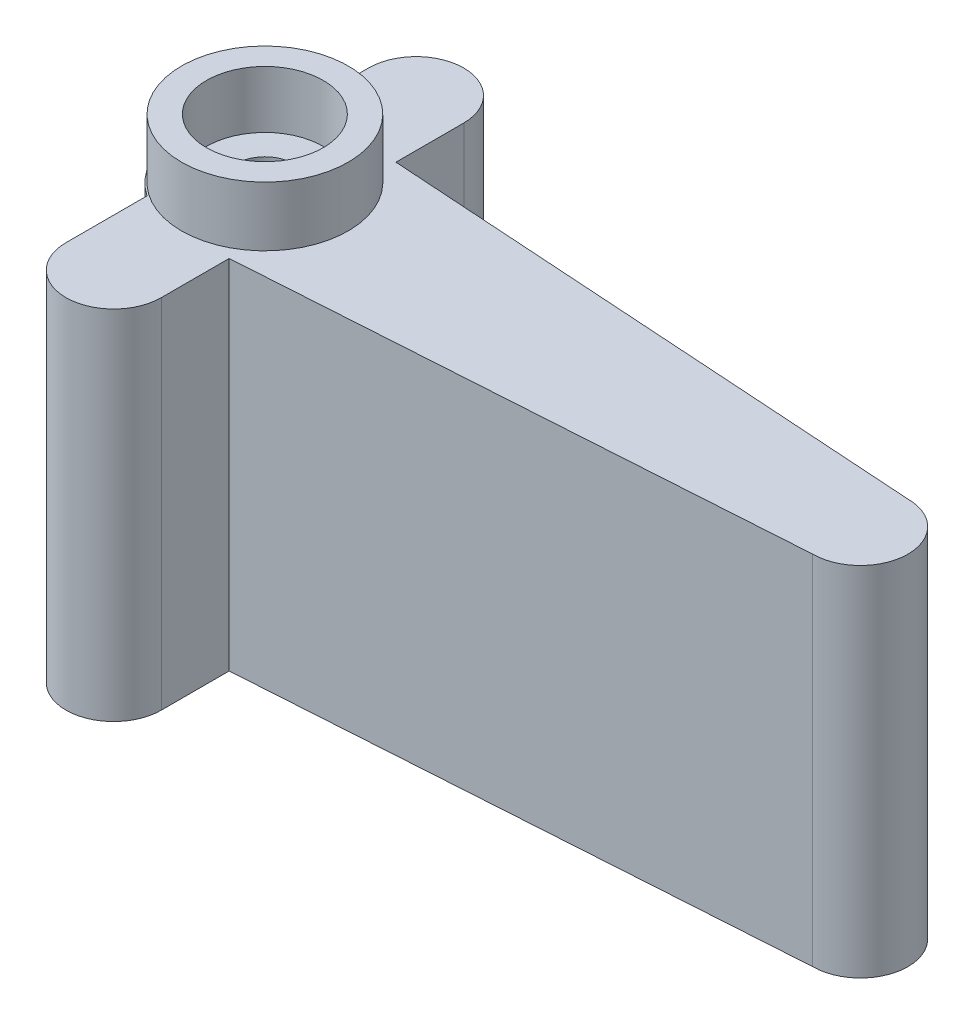
SolidWorks part; units mm, degrees
other "Camera1"
material "ABS"
ref_plane "Front Plane" through (0, 0, 0) normal (0, 0, 1) x (1, 0, 0)
ref_plane "Top Plane" through (0, 0, 0) normal (0, 1, 0) x (1, 0, 0)
ref_plane "Right Plane" through (0, 0, 0) normal (1, 0, 0) x (0, 0, -1)
sketch "Sketch1" plane through (0, 0, 0) normal (0, 1, 0) x (1, 0, 0)
  line L0 (25, 2) -> (25, -2) construction
  line L1 (0, -8.35) -> (0, 8.35) construction
  line L4 (2, 6.35) -> (2, 3.5)
  line L5 (-2, 6.35) -> (-2, 2.95)
  line L6 (2, -6.35) -> (2, -3.5)
  line L7 (-2, -6.35) -> (-2, -2.95)
  line L10 (25, -2) -> (2, -3.5)
  line L11 (25, 2) -> (2, 3.5)
  line L13 (-3.5641, 0) -> (17.2, 0) construction
  circle A0 centre (0, 0) radius 3.5 construction
  arc A2 (25, 2) -> (25, -2) centre (25, 0) cw
  arc A3 (2, 6.35) -> (-2, 6.35) centre (0, 6.35) ccw
  arc A8 (2, -6.35) -> (-2, -6.35) centre (0, -6.35) cw
  arc A24 (-2, 2.95) -> (-2, -2.95) centre (0, 0) ccw
  point P8 (0, 0)
  point P25 (0, 6.85)
  point P26 (0, 4.05)
  dimension "D1" = 7
  dimension "D2" = 25
  dimension "D3" = 16.7
  dimension "D5" = 2
  dimension "D7" = 2.8
  dimension "D8" = 7
  dimension "D10" = 5.9
extrude "Boss-Extrude1" add sketch "Sketch1" along normal blind 15
sketch "Sketch2" plane through (0, 0, 0) normal (0, -1, 0) x (1, 0, 0)
  circle A0 centre (0, 0) radius 2.35
  dimension "D1" = 4.7
extrude "Cut-Extrude1" cut sketch "Sketch2" against normal blind 1
sketch "Sketch3" plane through (0, 15, 0) normal (0, 1, 0) x (1, 0, 0)
  circle A0 centre (0, 0) radius 2.45
  circle A1 centre (0, 0) radius 3.5
  dimension "D1" = 4.9
  dimension "D2" = 7
extrude "Boss-Extrude2" add sketch "Sketch3" along normal blind 2.5
sketch "Sketch4" plane through (0, 15, 0) normal (0, 1, 0) x (1, 0, 0)
  circle A0 centre (0, 0) radius 1.2
  dimension "D1" = 2.4
extrude "Cut-Extrude2" cut sketch "Sketch4" against normal through all
sketch "Sketch5" plane through (0, 15, 0) normal (0, 1, 0) x (1, 0, 0)
  circle A0 centre (0, 0) radius 1.2 construction
  circle A1 centre (0, 0) radius 2.45
  circle A2 centre (0, 0) radius 2.45
  circle A3 centre (0, 0) radius 1.2
  dimension "D1" = 0
extrude "Boss-Extrude3" add sketch "Sketch5" along normal blind 0.1
